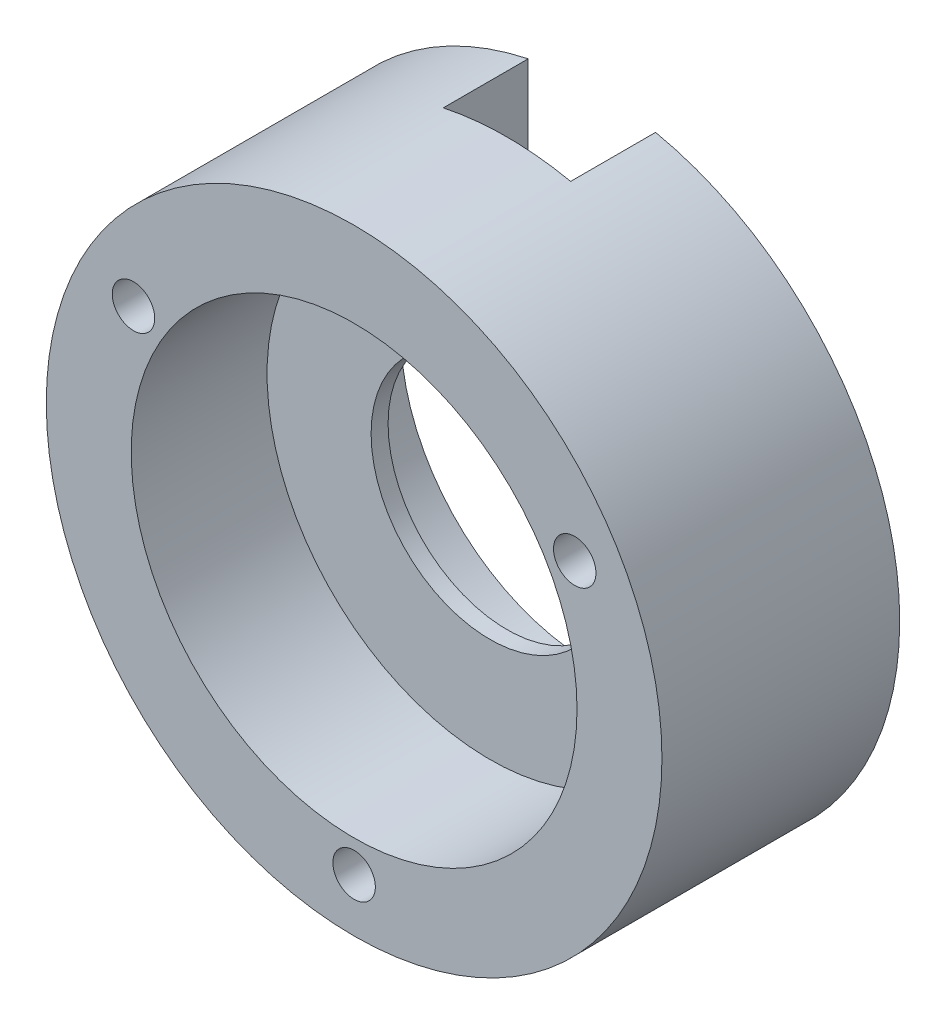
SolidWorks part; units mm, degrees
ref_plane "Ön Düzlem" through (0, 0, 0) normal (0, 0, 1) x (1, 0, 0)
ref_plane "Üst Düzlem" through (0, 0, 0) normal (0, 1, 0) x (1, 0, 0)
ref_plane "Sağ Düzlem" through (0, 0, 0) normal (1, 0, 0) x (0, 0, -1)
sketch "Sketch1" plane through (0, 0, 0) normal (0, 0, 1) x (1, 0, 0)
  circle A0 centre (0, 0) radius 26.25
  circle A1 centre (0, 0) radius 36.25
  dimension "D1" = 52.5
  dimension "D2" = 10
extrude "Boss-Extrude1" add sketch "Sketch1" along normal blind 16
sketch "Sketch2" plane through (0, 0, 0) normal (0, 0, -1) x (-1, 0, 0)
  circle A0 centre (0, 0) radius 36.25 construction
  circle A1 centre (0, 0) radius 36.25
  circle A2 centre (0, 0) radius 14
  dimension "D1" = 28
extrude "Boss-Extrude2" add sketch "Sketch2" along normal blind 12
sketch "Sketch4" plane through (0, 0, -12) normal (0, 0, -1) x (-1, 0, 0)
  line L1 (7.5, 38) -> (-7.5, 38)
  line L2 (7.5, 38) -> (7.5, 8)
  line L3 (7.5, 8) -> (-7.5, 8)
  line L4 (-7.5, 38) -> (-7.5, 8)
  point P4 (0, 8)
  dimension "D1" = 15
  dimension "D2" = 30
  dimension "D3" = 8
extrude "Cut-Extrude1" cut sketch "Sketch4" against normal blind 10
sketch "Sketch5" plane through (0, 0, -12) normal (0, 0, -1) x (-1, 0, 0)
  circle A0 centre (0, 0) radius 22.5
  dimension "D1" = 45
extrude "Cut-Extrude2" cut sketch "Sketch5" against normal up to surface (10 mm away) up to face at (0, 24.3843, -2)
sketch "Sketch7" plane through (0, 0, -12) normal (0, 0, -1) x (-1, 0, 0)
  line L1 (0, 0) -> (-25.9808, 15) construction
  line L2 (0, 0) -> (0, 9.4177) construction
  circle A0 centre (-25.9808, 15) radius 2.5
  circle A1 centre (0, 0) radius 30 construction
  circle A2 centre (25.9808, 15) radius 2.5
  circle A3 centre (0, -30) radius 2.5
  point P13 (0, 0)
  dimension "D1" = 5
  dimension "D2" = 60
  dimension "D3" = 60
  dimension "D4" = 3
extrude "Cut-Extrude3" cut sketch "Sketch7" against normal through all
